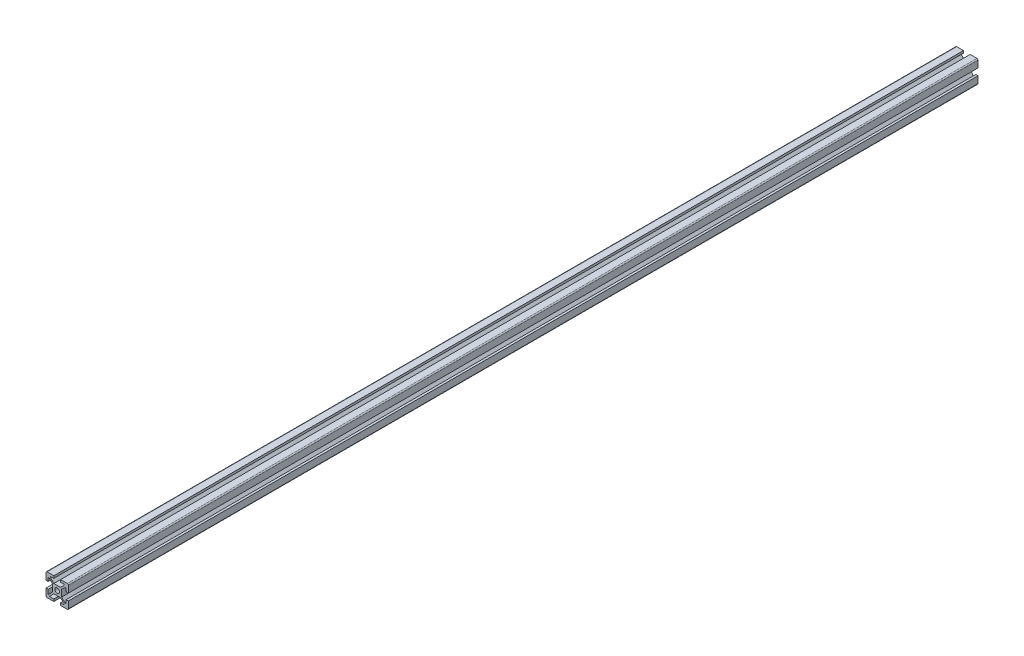
SolidWorks part; units mm, degrees
ref_plane "Front Plane" through (0, 0, 0) normal (0, 0, 1) x (1, 0, 0)
ref_plane "Top Plane" through (0, 0, 0) normal (0, 1, 0) x (1, 0, 0)
ref_plane "Right Plane" through (0, 0, 0) normal (1, 0, 0) x (0, 0, -1)
sketch "Sketch1" plane through (0, 0, 0) normal (0, 0, 1) x (1, 0, 0)
  line L0 (0, 10) -> (0, -10) construction
  line L1 (10, 10) -> (-10, 10)
  line L2 (10, 10) -> (10, -10)
  line L3 (10, -10) -> (-10, -10)
  line L4 (-10, 10) -> (-10, -10)
  line L5 (10, 10) -> (-10, -10) construction
  line L6 (10, -10) -> (-10, 10) construction
  line L7 (-10, 0) -> (10, 0) construction
  line L8 (-4, 3) -> (-8, 7)
  line L9 (6, 6) -> (-6, 6)
  line L10 (6, 6) -> (6, -6)
  line L11 (6, -6) -> (-6, -6)
  line L12 (-6, 6) -> (-6, -6)
  line L13 (6, 6) -> (-6, -6) construction
  line L14 (6, -6) -> (-6, 6) construction
  line L15 (4, 4) -> (-4, 4)
  line L16 (4, 4) -> (4, -4)
  line L17 (4, -4) -> (-4, -4)
  line L18 (-4, 4) -> (-4, -4)
  line L19 (4, 4) -> (-4, -4) construction
  line L20 (4, -4) -> (-4, 4) construction
  line L21 (3, 10) -> (-3, 10)
  line L22 (3, 10) -> (3, -10)
  line L23 (3, -10) -> (-3, -10)
  line L24 (-3, 10) -> (-3, -10)
  line L25 (3, 10) -> (-3, -10) construction
  line L26 (3, -10) -> (-3, 10) construction
  line L27 (10, 3) -> (-10, 3)
  line L28 (10, 3) -> (10, -3)
  line L29 (10, -3) -> (-10, -3)
  line L30 (-10, 3) -> (-10, -3)
  line L31 (10, 3) -> (-10, -3) construction
  line L32 (10, -3) -> (-10, 3) construction
  line L33 (8, 8) -> (-8, 8)
  line L34 (8, 8) -> (8, -8)
  line L35 (8, -8) -> (-8, -8)
  line L36 (-8, 8) -> (-8, -8)
  line L37 (8, 8) -> (-8, -8) construction
  line L38 (8, -8) -> (-8, 8) construction
  line L39 (-3, 4) -> (-7, 8)
  line L40 (3, 4) -> (7, 8)
  line L41 (4, 3) -> (8, 7)
  line L42 (-4, -3) -> (-8, -7)
  line L43 (-3, -4) -> (-7, -8)
  line L44 (3, -4) -> (7, -8)
  line L45 (4, -3) -> (8, -7)
  line L46 (-6, 6) -> (-6, 8)
  line L47 (-6, 6) -> (-8, 6)
  line L48 (-6, -6) -> (-8, -6)
  line L49 (-6, -6) -> (-6, -8)
  line L50 (6, -6) -> (6, -8)
  line L51 (6, -6) -> (8, -6)
  line L52 (6, 6) -> (6, 8)
  line L53 (6, 6) -> (8, 6)
  circle A0 centre (0, 0) radius 2.1
  point P0 (0, 0)
  point P10 (0, 0)
  point P15 (0, 0)
  point P20 (0, 0)
  point P25 (0, 0)
  point P30 (0, 0)
  dimension "D11" = 4.2
  dimension "D1" = 20
  dimension "D2" = 20
  dimension "D3" = 12
  dimension "D4" = 12
  dimension "D5" = 8
  dimension "D6" = 8
  dimension "D7" = 6
  dimension "D8" = 6
  dimension "D9" = 2
  dimension "D10" = 2
extrude "Boss-Extrude1" add sketch "Sketch1" along normal blind 812.8 contours L39 L46 L33 | L47 L46 L39 L33 L36 L8 | L47 L8 L36 | L36 L33 L24 L1 L4 L27 | L12 L47 L8 | L46 L9 L39 | L15 L39 L9 L12 L8 L18 | L27 L24 L15 L18 | L27 L22 L15 L24 | L29 L24 L27 L18 | L29 L22 L27 L24 A0 | L27 L16 L15 L22 | L16 L41 L10 L9 L40 L15 | L9 L52 L40 | L53 L10 L41 | L52 L53 L41 L34 L33 L40 | L52 L40 L33 | L41 L53 L34 | L33 L34 L27 L2 L1 L22 | L29 L16 L27 L22 | L16 L29 L22 L17 | L45 L16 L17 L44 L11 L10 | L10 L51 L45 | L50 L11 L44 | L51 L50 L44 L35 L34 L45 | L44 L50 L35 | L51 L45 L34 | L34 L35 L22 L3 L2 L29 | L22 L29 L24 L17 | L24 L29 L18 L17 | L43 L17 L18 L42 L12 L11 | L11 L49 L43 | L48 L12 L42 | L49 L48 L42 L36 L35 L43 | L36 L29 L4 L3 L24 L35
fillet "Fillet1" radius 1 4 edges at (-10, 10, 406.4) (-10, -10, 406.4) (10, -10, 406.4) (10, 10, 406.4)
